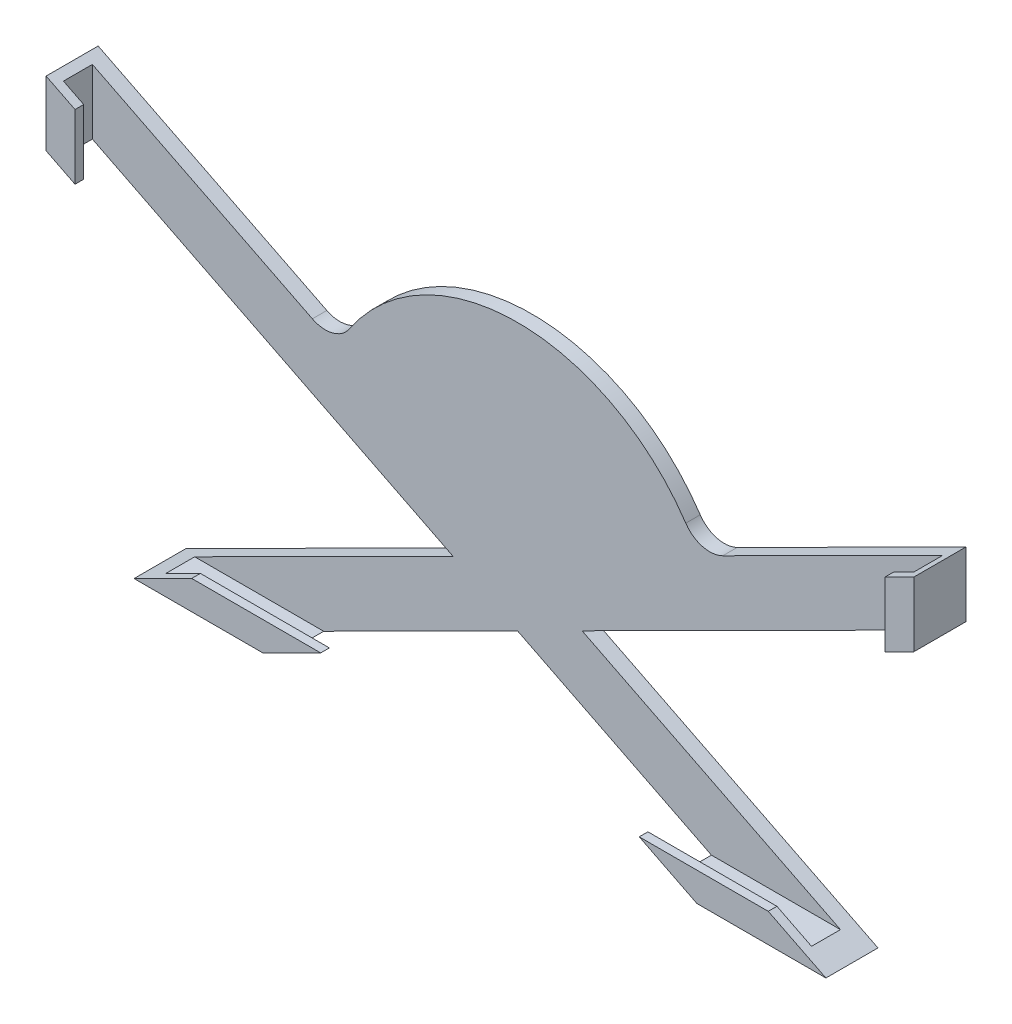
SolidWorks part; units mm, degrees
ref_plane "Front Plane" through (0, 0, 0) normal (0, 0, 1) x (1, 0, 0)
ref_plane "Top Plane" through (0, 0, 0) normal (0, 1, 0) x (1, 0, 0)
ref_plane "Right Plane" through (0, 0, 0) normal (1, 0, 0) x (0, 0, -1)
sketch "Sketch1" plane through (0, 0, 0) normal (0, 0, 1) x (1, 0, 0)
  line L0 (-150, 75.2489) -> (0, 0)
  line L3 (-150, 52.8734) -> (-22.3015, -11.1878)
  line L6 (150, 52.8734) -> (22.3015, -11.1878)
  line L9 (150, 75.2489) -> (0, 0)
  line L12 (0, 0) -> (0, -22.3755) construction
  line L13 (75, -60) -> (119.6031, -60)
  line L14 (0, -60) -> (0, -22.3755) construction
  line L15 (-119.6031, -60) -> (-75, -60)
  line L17 (-75, -60) -> (75, -60) construction
  line L18 (-150, 75.2489) -> (150, 75.2489) construction
  line L20 (-150, 75.2489) -> (-150, 52.8734)
  line L21 (150, 75.2489) -> (150, 52.8734)
  line L26 (-22.3015, -11.1878) -> (-119.6031, -60)
  line L27 (0, -22.3755) -> (75, -60)
  line L28 (22.3015, -11.1878) -> (119.6031, -60)
  line L29 (0, -22.3755) -> (-75, -60)
  line L30 (-22.3015, -11.1878) -> (0, -22.3755) construction
  line L31 (22.3015, -11.1878) -> (0, -22.3755) construction
  line L32 (0, 0) -> (22.3015, -11.1878) construction
  line L33 (0, 0) -> (-22.3015, -11.1878) construction
  point P1 (78.3054, -67.6107)
  point P2 (100.1704, -36.5916)
  dimension "D1" = 60
  dimension "D2" = 20
  dimension "D4" = 300
  dimension "D5" = 150
extrude "Boss-Extrude1" add sketch "Sketch1" along normal blind 5
sketch "Sketch2" plane through (0, 0, 5) normal (0, 0, 1) x (1, 0, 0)
  line L0 (-150, 75.2489) -> (-150, 52.8734)
  line L1 (-150, 52.8734) -> (-147, 51.3684)
  line L2 (-150, 52.8734) -> (-22.3015, -11.1878) construction
  line L3 (-147, 51.3684) -> (-147, 73.7439)
  line L4 (0, 0) -> (-150, 75.2489) construction
  line L5 (-147, 73.7439) -> (-150, 75.2489)
  line L6 (150, 75.2489) -> (147, 73.7439)
  line L7 (150, 75.2489) -> (0, 0) construction
  line L8 (147, 73.7439) -> (147, 51.3684)
  line L9 (22.3015, -11.1878) -> (150, 52.8734) construction
  line L10 (147, 51.3684) -> (150, 52.8734)
  line L11 (150, 52.8734) -> (150, 75.2489)
  line L12 (119.6031, -60) -> (111.6295, -56)
  line L13 (119.6031, -60) -> (22.3015, -11.1878) construction
  line L14 (111.6295, -56) -> (67.0265, -56)
  line L15 (0, -22.3755) -> (75, -60) construction
  line L16 (67.0265, -56) -> (75, -60)
  line L17 (75, -60) -> (119.6031, -60)
  line L18 (-75, -60) -> (-119.6031, -60)
  line L19 (-75, -60) -> (0, -22.3755) construction
  line L20 (-119.6031, -60) -> (-111.6295, -56)
  line L21 (-22.3015, -11.1878) -> (-119.6031, -60) construction
  line L22 (-111.6295, -56) -> (-67.0265, -56)
  line L23 (-67.0265, -56) -> (-75, -60)
  line L24 (-67.0265, -56) -> (67.0265, -56) construction
  point P35 (-74.3591, -60)
  dimension "D1" = 4
  dimension "D2" = 3
  dimension "D3" = 3
extrude "Boss-Extrude2" add sketch "Sketch2" along normal blind 10
sketch "Sketch3" plane through (0, 0, 15) normal (0, 0, 1) x (1, 0, 0)
  line L0 (-150, 75.2489) -> (-150, 52.8734)
  line L1 (-150, 52.8734) -> (-140, 47.8568)
  line L2 (-147, 51.3684) -> (-22.3015, -11.1878) construction
  line L3 (-140, 47.8568) -> (-140, 70.2323)
  line L4 (0, 0) -> (-147, 73.7439) construction
  line L5 (-140, 70.2323) -> (-150, 75.2489)
  line L6 (-75, -60) -> (-55.0662, -50)
  line L7 (-67.0265, -56) -> (0, -22.3755) construction
  line L8 (-55.0662, -50) -> (-99.6692, -50)
  line L9 (-22.3015, -11.1878) -> (-111.6295, -56) construction
  line L10 (-99.6692, -50) -> (-119.6031, -60)
  line L11 (-119.6031, -60) -> (-75, -60)
  line L12 (75, -60) -> (119.6031, -60)
  line L13 (119.6031, -60) -> (99.6692, -50)
  line L14 (111.6295, -56) -> (22.3015, -11.1878) construction
  line L15 (99.6692, -50) -> (55.0662, -50)
  line L16 (0, -22.3755) -> (67.0265, -56) construction
  line L17 (55.0662, -50) -> (75, -60)
  line L18 (-55.0662, -50) -> (55.0662, -50) construction
  line L19 (150, 75.2489) -> (140, 70.2323)
  line L20 (147, 73.7439) -> (0, 0) construction
  line L21 (140, 70.2323) -> (140, 47.8568)
  line L22 (22.3015, -11.1878) -> (147, 51.3684) construction
  line L23 (140, 47.8568) -> (150, 52.8734)
  line L24 (150, 52.8734) -> (150, 75.2489)
  dimension "D1" = 10
  dimension "D2" = 10
  dimension "D3" = 10
extrude "Boss-Extrude3" add sketch "Sketch3" along normal blind 3
sketch "Sketch4" plane through (0, 0, 0) normal (0, 0, 1) x (1, 0, 0)
  line L0 (0, 0) -> (-147, 73.7439) construction
  line L1 (147, 73.7439) -> (0, 0) construction
  line L2 (-62.5683, 31.388) -> (0, 0)
  line L3 (0, 0) -> (62.5683, 31.388)
  arc A0 (-62.5683, 31.388) -> (62.5683, 31.388) centre (0, 0) cw
  dimension "D1" = 70
extrude "Boss-Extrude4" add sketch "Sketch4" along normal blind 5
fillet "Fillet1" radius 10 2 edges at (-62.5683, 31.388, 2.5) (62.5683, 31.388, 2.5)
